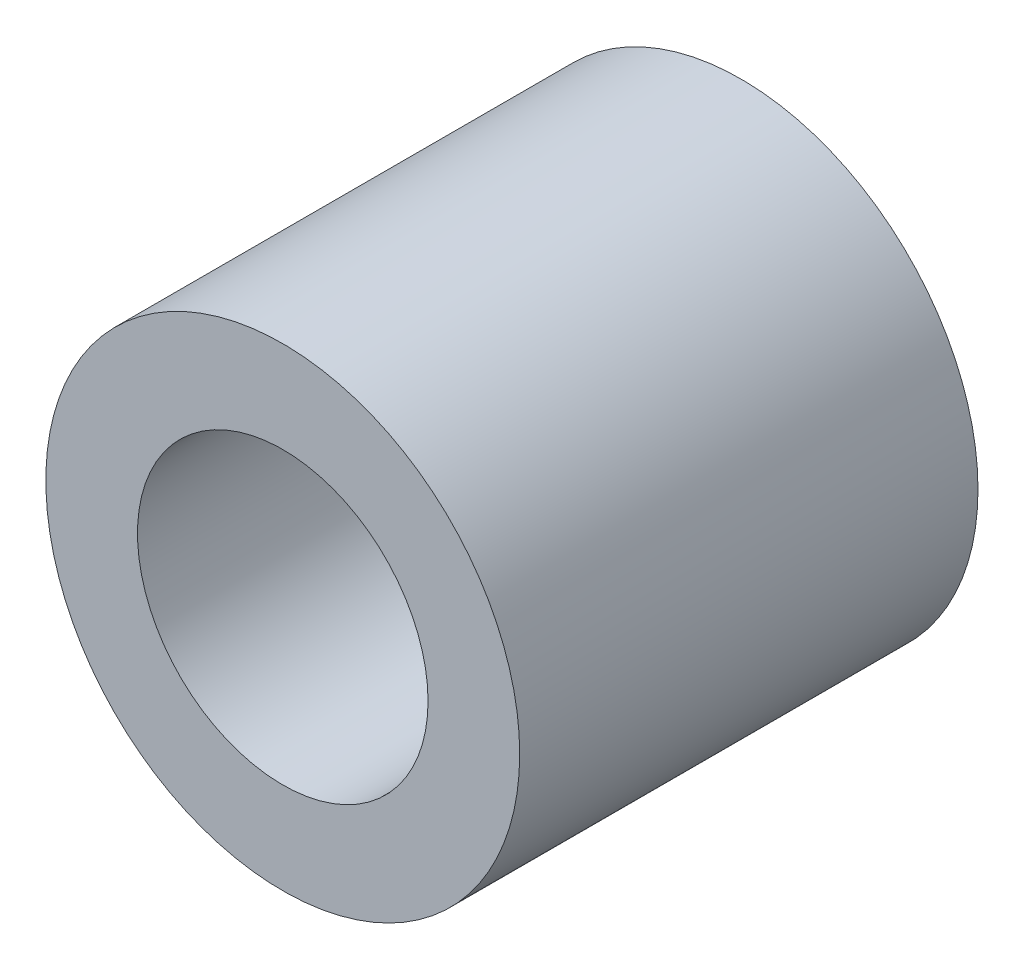
SolidWorks part; units mm, degrees
ref_plane "前视基准面" through (0, 0, 0) normal (0, 0, 1) x (1, 0, 0)
ref_plane "上视基准面" through (0, 0, 0) normal (0, 1, 0) x (1, 0, 0)
ref_plane "右视基准面" through (0, 0, 0) normal (1, 0, 0) x (0, 0, -1)
sketch "草图1" plane through (0, 0, 0) normal (0, 0, 1) x (1, 0, 0)
  circle A0 centre (0, 0) radius 1.585
  circle A1 centre (0, 0) radius 2.585
  dimension "D1" = 3.17
  dimension "D2" = 1
extrude "凸台-拉伸1" add sketch "草图1" along normal blind 5
